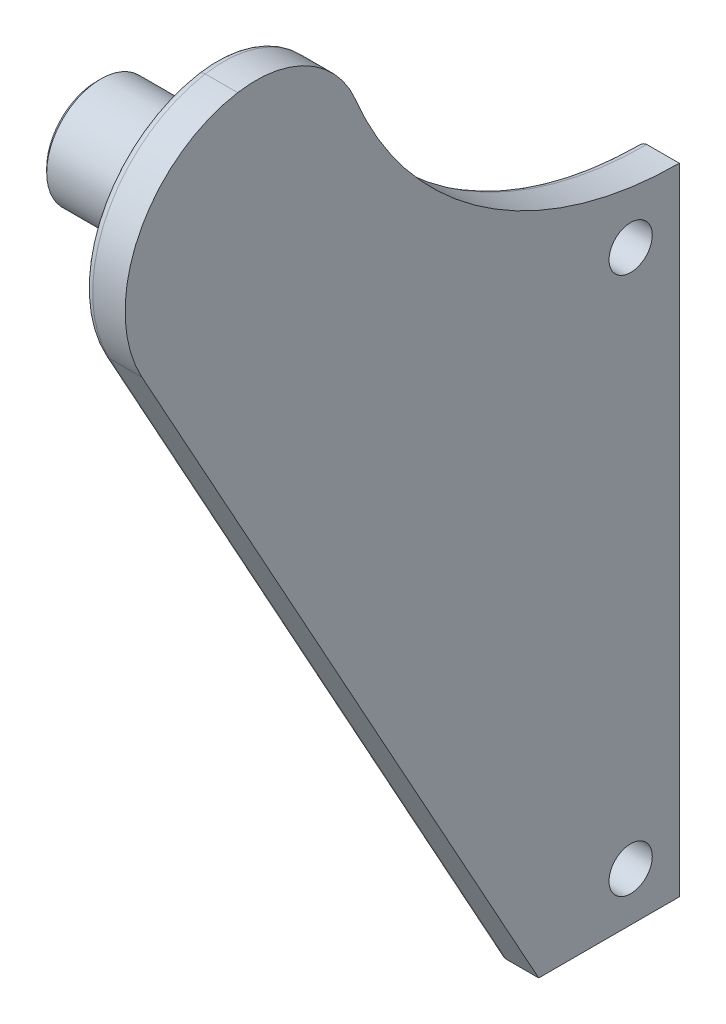
SolidWorks part; units mm, degrees
material "PET"
ref_plane "Ebene vorne" through (0, 0, 0) normal (0, 0, 1) x (1, 0, 0)
ref_plane "Ebene oben" through (0, 0, 0) normal (0, 1, 0) x (1, 0, 0)
ref_plane "Ebene rechts" through (0, 0, 0) normal (1, 0, 0) x (0, 0, -1)
sketch "Skizze1" plane through (0, 0, 0) normal (1, 0, 0) x (0, 0, -1)
  line L0 (31, -11) -> (31, -58)
  line L1 (31, -58) -> (20.6, -58)
  line L2 (20.6, -58) -> (-8.7543, -4.8334)
  line L3 (31, -11) -> (6.0509, 7.9616)
  arc A0 (6.0509, 7.9616) -> (-8.7543, -4.8334) centre (0, 0) ccw
  dimension "D1" = 20
  dimension "D2" = 10.4
  dimension "D3" = 47
  dimension "D4" = 31
  dimension "D5" = 58
extrude "Aufsatz-Linear austragen1" add sketch "Skizze1" along normal blind 3
sketch "Skizze2" plane through (0, 0, 0) normal (-1, 0, 0) x (0, 0, 1)
  circle A0 centre (0, 0) radius 4
  dimension "D1" = 8
extrude "Aufsatz-Linear austragen2" add sketch "Skizze2" along normal blind 9.1
chamfer "Fase1" distance 0.3 angle 45 1 edges at (-9.1, 0, 4)
sketch "Skizze3" plane through (3, 0, 0) normal (1, 0, 0) x (0, 0, -1)
  line L0 (31, -11) -> (-5.3496, -11) construction
  line L1 (-8.7543, -4.8334) -> (20.6, -58) construction
  line L2 (31, -58) -> (31, -11) construction
  line L3 (20.6, -58) -> (31, -58) construction
  circle A0 centre (27.4, -54.4) radius 3.6 construction
  circle A1 centre (27.4, -54.4) radius 1.6
  circle A2 centre (27.4, -14.6) radius 3.6 construction
  circle A3 centre (27.4, -14.6) radius 1.6
  dimension "D1" = 3.2
  dimension "D2" = 3.2
  dimension "D3" = 7.2
  dimension "D4" = 7.2
extrude "Schnitt-Linear austragen1" cut sketch "Skizze3" against normal blind 6
sketch "Skizze4" plane through (0, 0, 0) normal (-1, 0, 0) x (0, 0, 1)
  circle A0 centre (0, 0) radius 7
  dimension "D1" = 14
extrude "Aufsatz-Linear austragen3" add sketch "Skizze4" along normal blind 1.2
fillet "Verrundung1" radius 1 1 edges at (0, 0, -7)
sketch "Skizze5" plane through (0, 0, 0) normal (-1, 0, 0) x (0, 0, 1)
  line L0 (-31, -11) -> (5.3496, -11) construction
  line L1 (8.7543, -4.8334) -> (-20.6, -58) construction
  line L2 (-31, -11) -> (-6.0509, 7.9616) construction
  line L3 (-31, -11) -> (-6.0509, 7.9616)
  arc A0 (-31, -11) -> (-6.0509, 7.9616) centre (-31, 14.8945) ccw
  line M5 (-6.0509, 7.9616) -> (-31, -11)
extrude "Schnitt-Linear austragen2" cut sketch "Skizze5" against normal blind 10 contours A0 M5
fillet "Verrundung3" radius 8 1 edges at (1.5, 7.9616, -6.0509)
fillet "Verrundung4" radius 0.6 6 edges at (0, -31.4167, -5.9228) (0, 4.3423, 9.008) (0, 8.97, -3.542) (0, -58, -25.8) (0, -34.5, -31) (0, -6.6249, -16.5972)
fillet "Verrundung5" radius 0.6 1 edges at (-1.2, 0, 7)
